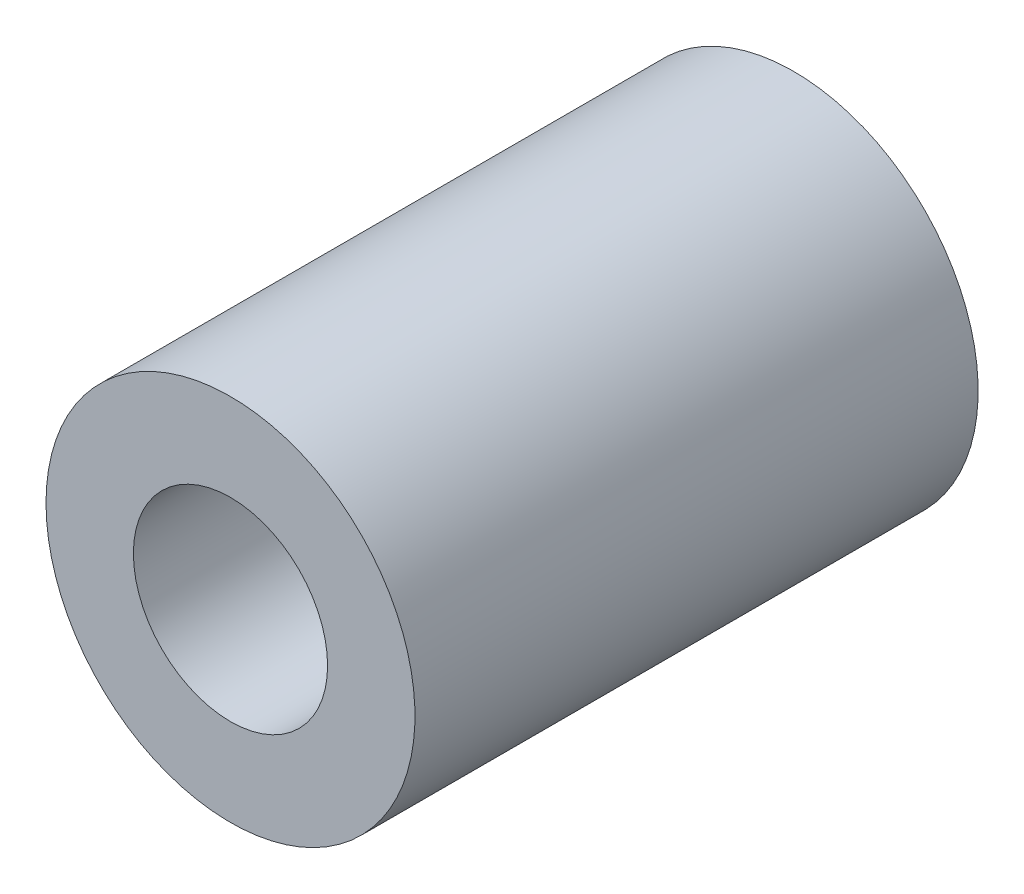
SolidWorks part; units mm, degrees
ref_plane "前视基准面" through (0, 0, 0) normal (0, 0, 1) x (1, 0, 0)
ref_plane "上视基准面" through (0, 0, 0) normal (0, 1, 0) x (1, 0, 0)
ref_plane "右视基准面" through (0, 0, 0) normal (1, 0, 0) x (0, 0, -1)
sketch "草图1" plane through (0, 0, 0) normal (0, 0, 1) x (1, 0, 0)
  circle A0 centre (0, 0) radius 5
  circle A1 centre (0, 0) radius 9.5
  dimension "D1" = 10
  dimension "D2" = 19
extrude "凸台-拉伸1" add sketch "草图1" along normal blind 29
